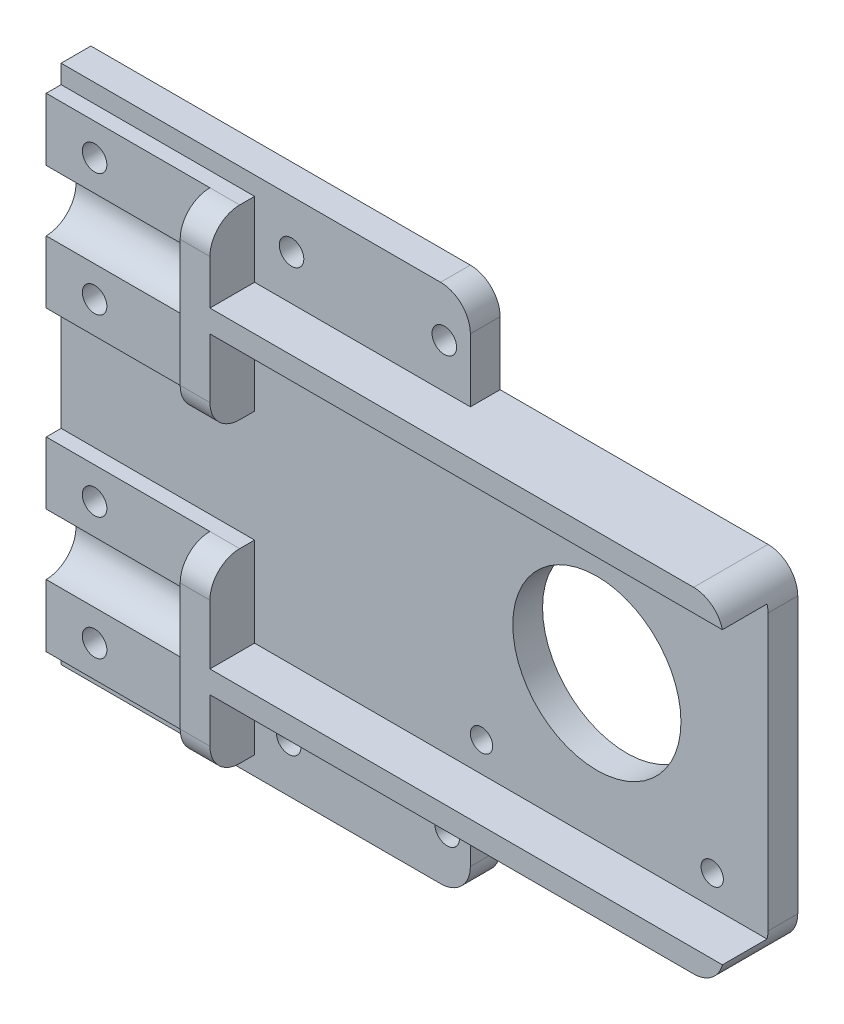
SolidWorks part; units mm, degrees
ref_plane "Front Plane" through (0, 0, 0) normal (0, 0, 1) x (1, 0, 0)
ref_plane "Top Plane" through (0, 0, 0) normal (0, 1, 0) x (1, 0, 0)
ref_plane "Right Plane" through (0, 0, 0) normal (1, 0, 0) x (0, 0, -1)
sketch "Sketch1" plane through (0, 0, 0) normal (0, 0, 1) x (1, 0, 0)
  line L1 (-27.5, 35) -> (27.5, 35)
  line L2 (-27.5, 35) -> (-27.5, -35)
  line L3 (-27.5, -35) -> (27.5, -35)
  line L4 (27.5, 35) -> (27.5, -35)
  line L5 (-27.5, 35) -> (27.5, -35) construction
  line L6 (-27.5, -35) -> (27.5, 35) construction
  point P0 (0, 0)
  dimension "D1" = 70
  dimension "D2" = 55
extrude "Boss-Extrude1" add sketch "Sketch1" along normal blind 4
sketch "Sketch4" plane through (0, 0, 4) normal (0, 0, 1) x (1, 0, 0)
  line L0 (-27.5, 35) -> (-27.5, -35) construction
  line L1 (-27.5, 7.5) -> (-1.5, 7.5)
  line L2 (-27.5, 7.5) -> (-27.5, 32.5)
  line L3 (-27.5, 32.5) -> (-1.5, 32.5)
  line L4 (-1.5, 7.5) -> (-1.5, 32.5)
  line L5 (-27.5, -20) -> (-15.496, -20) construction
  line L6 (-27.5, -7.5) -> (-1.5, -7.5)
  line L7 (-27.5, -7.5) -> (-27.5, -32.5)
  line L8 (-27.5, -32.5) -> (-1.5, -32.5)
  line L9 (-1.5, -7.5) -> (-1.5, -32.5)
  line L10 (-15.496, -20) -> (-15.496, 20) construction
  line L11 (-15.496, 20) -> (-27.5, 20) construction
  line L12 (-15.496, 0) -> (0, 0) construction
  dimension "D1" = 40
  dimension "D2" = 25
  dimension "D3" = 26
extrude "Boss-Extrude2" add sketch "Sketch4" along normal blind 2
sketch "Sketch3" plane through (-27.5, 0, 0) normal (-1, 0, 0) x (0, 0, 1)
  line L0 (2, 20) -> (2, -20) construction
  line L3 (2, 20) -> (6.1, 20) construction
  line L5 (6, 32.5) -> (6, 7.5) construction
  line L6 (2, -20) -> (6.1, -20) construction
  line L7 (2, 0) -> (0, 0) construction
  line L8 (4, 35) -> (4, 32.5) construction
  circle A0 centre (6.1, 20) radius 4.1
  circle A1 centre (6.1, -20) radius 4.1
  point P13 (6, 20)
  dimension "D1" = 8.2
  dimension "D3" = 2
extrude "Cut-Extrude1" cut sketch "Sketch3" against normal blind 22
sketch "Sketch5" plane through (0, 0, 4) normal (0, 0, 1) x (1, 0, 0)
  line L0 (27.5, -35) -> (27.5, 35) construction
  line L1 (27.5, -22.5) -> (67.5, -22.5)
  line L2 (27.5, -22.5) -> (27.5, 22.5)
  line L3 (27.5, 22.5) -> (67.5, 22.5)
  line L4 (67.5, -22.5) -> (67.5, 22.5)
  line L5 (67.5, 0) -> (0, 0) construction
  dimension "D1" = 40
  dimension "D2" = 45
extrude "Boss-Extrude3" add sketch "Sketch5" against normal up to surface (4 mm away) up to face at (0, 0, 0)
sketch "Sketch7" plane through (0, 0, 0) normal (0, 0, -1) x (-1, 0, 0)
  line L0 (-29, -15.5) -> (-60, -15.5) construction
  line L1 (-44.5, 0) -> (-67.5, 0) construction
  line L2 (-67.5, 22.5) -> (-67.5, -22.5) construction
  circle B0 centre (-44.5, 0) radius 11.3
  circle B1 centre (-60, 15.5) radius 1.5
  circle B2 centre (-29, 15.5) radius 1.5
  circle B3 centre (-29, -15.5) radius 1.5
  circle B4 centre (-60, -15.5) radius 1.5
  dimension "D1" = 23
sketch_block_instance "Block1-1"
sketch_block "Block1"
extrude "Cut-Extrude2" cut sketch "Sketch7" against normal through all
fillet "Fillet1" radius 4 2 edges at (27.5, -35, 2) (27.5, 35, 2)
sketch "Sketch8" plane through (0, 0, 6) normal (0, 0, 1) x (1, 0, 0)
  line L0 (-1.5, 32.5) -> (-27.5, 32.5) construction
  line L1 (-1.5, 7.5) -> (-5.5, 7.5)
  line L2 (-1.5, 7.5) -> (-1.5, 32.5)
  line L3 (-1.5, 32.5) -> (-5.5, 32.5)
  line L4 (-5.5, 7.5) -> (-5.5, 32.5)
  line L5 (-1.5, -7.5) -> (-27.5, -7.5) construction
  line L6 (-1.5, -32.5) -> (-5.5, -32.5)
  line L7 (-1.5, -32.5) -> (-1.5, -7.5)
  line L8 (-1.5, -7.5) -> (-5.5, -7.5)
  line L9 (-5.5, -32.5) -> (-5.5, -7.5)
extrude "Boss-Extrude4" add sketch "Sketch8" along normal blind 4
fillet "Fillet2" radius 4 4 edges at (-3.5, -32.5, 10) (-3.5, -7.5, 10) (-3.5, 32.5, 10) (-3.5, 7.5, 10)
sketch "Sketch10" plane through (0, 0, 4) normal (0, 0, 1) x (1, 0, 0)
  line L0 (-1.5, 7.5) -> (-1.5, 32.5) construction
  line L1 (67.5, 22.5) -> (-1.5, 22.5)
  line L2 (67.5, 22.5) -> (67.5, 19.5)
  line L3 (67.5, 19.5) -> (-1.5, 19.5)
  line L4 (-1.5, 22.5) -> (-1.5, 19.5)
  line L5 (-1.5, -32.5) -> (-1.5, -7.5) construction
  line L6 (67.5, -22.5) -> (-1.5, -22.5)
  line L7 (67.5, -22.5) -> (67.5, -19.5)
  line L8 (67.5, -19.5) -> (-1.5, -19.5)
  line L9 (-1.5, -22.5) -> (-1.5, -19.5)
  dimension "D1" = 3
extrude "Boss-Extrude5" add sketch "Sketch10" along normal up to surface (6 mm away) up to face at (-3.5, -20, 10)
sketch "Sketch12" plane through (0, 0, 4) normal (0, 0, 1) x (1, 0, 0)
  circle A1 centre (3.4661, 28.5) radius 1.65
  circle A2 centre (3.4661, 28.5) radius 1.65
  circle A3 centre (24, 28.5) radius 1.65
  circle A4 centre (24, 28.5) radius 1.65
  circle A5 centre (24.385, -28.5) radius 1.65
  circle A6 centre (24.385, -28.5) radius 1.65
  circle A7 centre (3.0811, -28.5) radius 1.65
  circle A8 centre (3.0811, -28.5) radius 1.65
  dimension "D1" = 0
  dimension "D2" = 0
  dimension "D3" = 0
  dimension "D4" = 0
sketch "Sketch13" plane through (0, 0, 0) normal (0, 0, -1) x (-1, 0, 0)
  circle A1 centre (21, -11.7619) radius 1.65
  circle A2 centre (21, -11.7619) radius 1.65
  circle A3 centre (21, -28.2381) radius 1.65
  circle A4 centre (21, -28.2381) radius 1.65
  circle A5 centre (21, 28.2381) radius 1.65
  circle A6 centre (21, 28.2381) radius 1.65
  circle A7 centre (21, 11.7619) radius 1.65
  circle A8 centre (21, 11.7619) radius 1.65
  dimension "D1" = 0
  dimension "D2" = 0
  dimension "D3" = 0
  dimension "D4" = 0
extrude "Cut-Extrude4" cut sketch "Sketch12" against normal through all both and the other way through all
extrude "Cut-Extrude5" cut sketch "Sketch13" against normal through all both and the other way through all
fillet "Fillet3" radius 4 2 edges at (67.5, 22.5, 5) (67.5, -22.5, 5)
